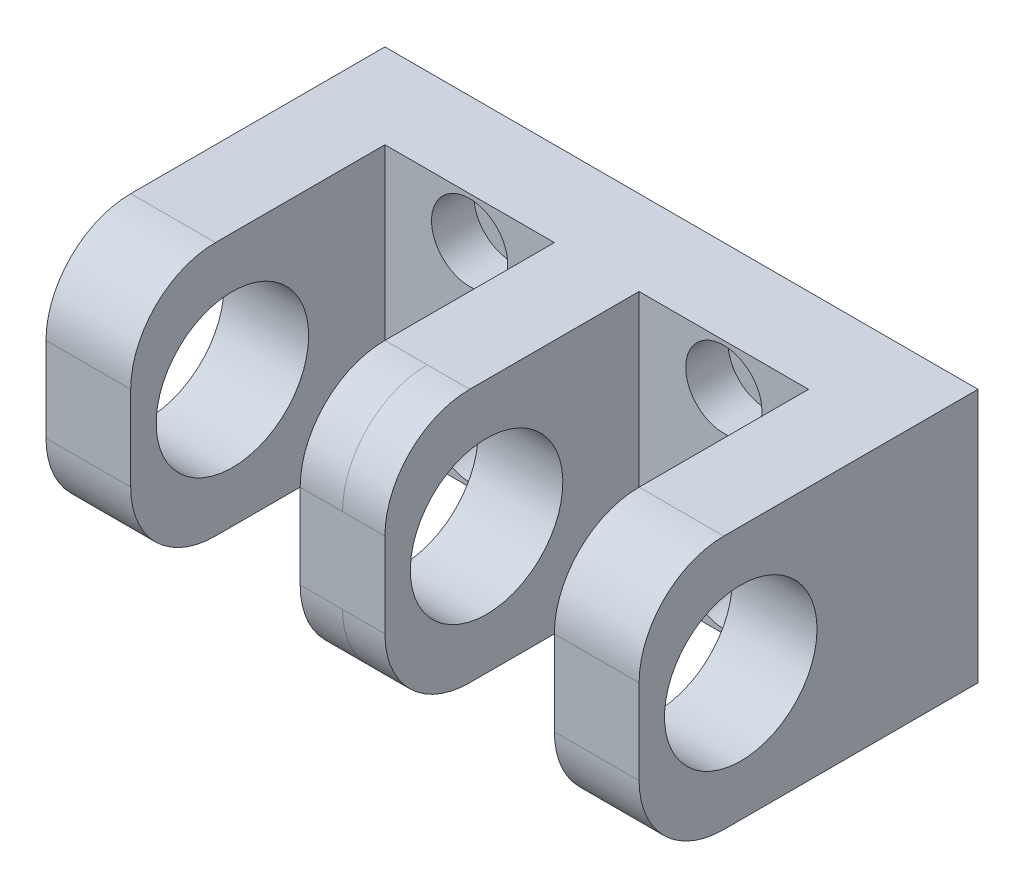
SolidWorks part; units mm, degrees
ref_plane "Płaszczyzna przednia" through (0, 0, 0) normal (0, 0, 1) x (1, 0, 0)
ref_plane "Płaszczyzna górna" through (0, 0, 0) normal (0, 1, 0) x (1, 0, 0)
ref_plane "Płaszczyzna prawa" through (0, 0, 0) normal (1, 0, 0) x (0, 0, -1)
sketch "Szkic1" plane through (0, 0, 0) normal (0, 0, 1) x (1, 0, 0)
  line L1 (0, 0) -> (35, 0)
  line L2 (0, 0) -> (0, 30)
  line L3 (0, 30) -> (35, 30)
  line L4 (35, 0) -> (35, 30)
  dimension "D1" = 35
  dimension "D2" = 30
extrude "Dodanie-wyciągnięcie1" add sketch "Szkic1" along normal blind 10
sketch "Szkic2" plane through (0, 0, 10) normal (0, 0, 1) x (1, 0, 0)
  line L0 (0, 0) -> (35, 0) construction
  line L1 (0, 30) -> (5, 30)
  line L2 (0, 30) -> (0, 0)
  line L3 (0, 0) -> (5, 0)
  line L4 (5, 30) -> (5, 0)
  line L5 (35, 30) -> (0, 30) construction
  line L6 (35, 0) -> (25, 0)
  line L7 (35, 0) -> (35, 30)
  line L8 (35, 30) -> (25, 30)
  line L9 (25, 0) -> (25, 30)
  dimension "D1" = 5
  dimension "D2" = 10
extrude "Dodanie-wyciągnięcie2" add sketch "Szkic2" along normal blind 30
sketch "Szkic3" plane through (35, 0, 0) normal (1, 0, 0) x (0, 0, -1)
  line L0 (-10, 0) -> (-10, 30) construction
  line L1 (-10, 0) -> (-10, 30)
  line L2 (-40, 30) -> (0, 30) construction
  circle A0 centre (-28, 15) radius 9
  dimension "D1" = 18
  dimension "D2" = 18
  dimension "D3" = 15
extrude "Wytnij-wyciągnięcie1" cut sketch "Szkic3" against normal through all contours A0
fillet "Zaokrąglenie1" radius 10 4 edges at (30, 0, 40) (2.5, 0, 40) (2.5, 30, 40) (30, 30, 40)
mirror "Lustro1" about plane through (0, 0, 10) normal (1, 0, 0) of "Dodanie-wyciągnięcie1", "Dodanie-wyciągnięcie2", "Wytnij-wyciągnięcie1", "Zaokrąglenie1"
sketch "Szkic4" plane through (0, 0, 10) normal (0, 0, 1) x (1, 0, 0)
  line L0 (-25, 30) -> (-5, 30) construction
  line L1 (-5, 0) -> (-5, 30) construction
  line L2 (5, 0) -> (5, 30) construction
  line L3 (-5, 0) -> (-25, 0) construction
  circle A0 centre (-15, 25) radius 2.5
  circle A1 centre (15, 25) radius 2.5
  circle A2 centre (15, 5) radius 2.5
  circle A3 centre (-15, 5) radius 2.5
  point P8 (0, 0)
  point P15 (0, 0)
  point P16 (0, 0)
  point P17 (15, 25)
  point P18 (0, 0)
  point P19 (15, 25)
  point P20 (-15, 6.9404)
  dimension "D1" = 5
  dimension "D3" = 10
  dimension "D2" = 5
  dimension "D4" = 10
  dimension "D5" = 5
extrude "Wytnij-wyciągnięcie2" cut sketch "Szkic4" against normal through all
sketch "Szkic5" plane through (0, 0, 10) normal (0, 0, 1) x (1, 0, 0)
  circle A0 centre (15, 25) radius 2.5 construction
  circle A1 centre (15, 5) radius 2.5 construction
  circle A2 centre (-15, 5) radius 2.5 construction
  circle A3 centre (-15, 25) radius 2.5 construction
  circle A4 centre (15, 25) radius 2.5
  circle A5 centre (15, 5) radius 2.5
  circle A6 centre (-15, 5) radius 2.5
  circle A7 centre (-15, 25) radius 2.5
  circle A8 centre (-15, 25) radius 4.5
  circle A9 centre (15, 25) radius 4.5
  circle A10 centre (15, 5) radius 4.5
  circle A11 centre (-15, 5) radius 4.5
  point P13 (0, 0)
  point P14 (0, 0)
  dimension "D1" = 9
extrude "Wytnij-wyciągnięcie3" cut sketch "Szkic5" against normal blind 5
